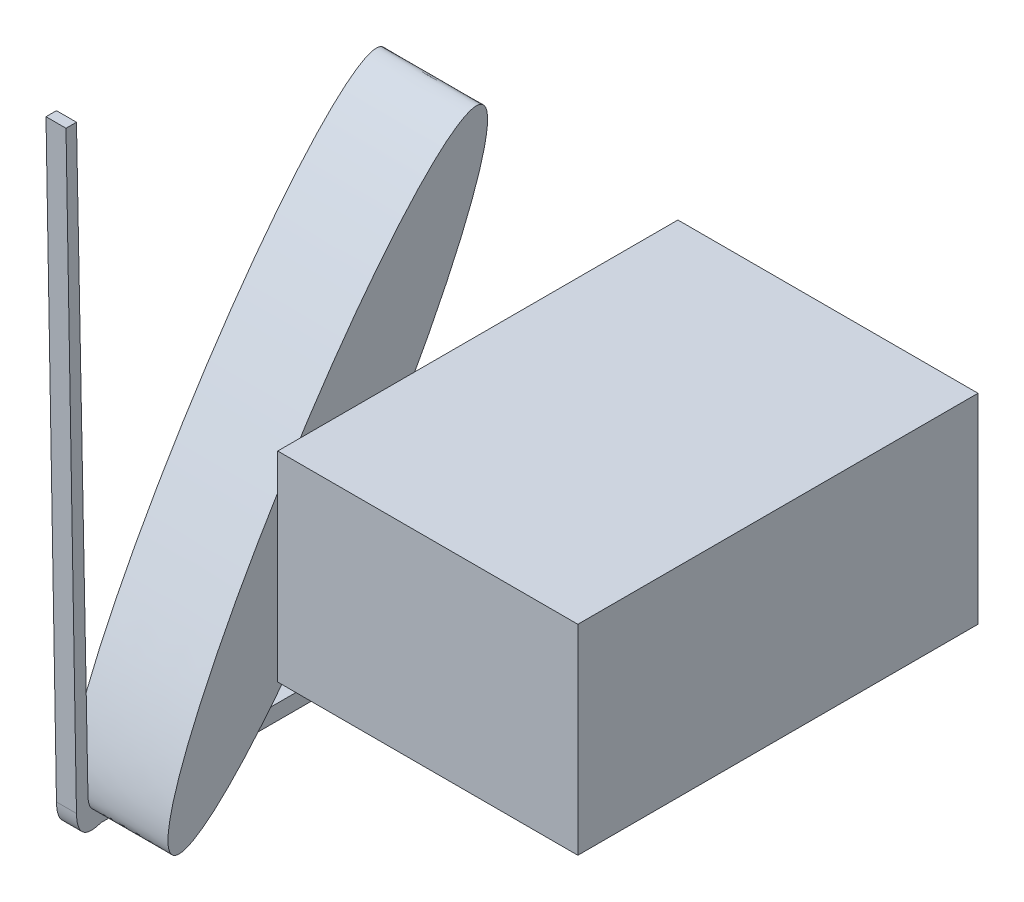
SolidWorks part; units mm, degrees
ref_plane "前视基准面" through (0, 0, 0) normal (0, 0, 1) x (1, 0, 0)
ref_plane "上视基准面" through (0, 0, 0) normal (0, 1, 0) x (1, 0, 0)
ref_plane "右视基准面" through (0, 0, 0) normal (1, 0, 0) x (0, 0, -1)
sketch "草图1" plane through (0, 0, 0) normal (0, 0, 1) x (1, 0, 0)
  line L1 (0, 0) -> (30, 0)
  line L2 (0, 0) -> (0, 20)
  line L3 (0, 20) -> (30, 20)
  line L4 (30, 0) -> (30, 20)
extrude "凸台-拉伸1" add sketch "草图1" along normal blind 40
sketch "草图2" plane through (0, 0, 0) normal (-1, 0, 0) x (0, 0, 1)
  circle A0 centre (30, 10) radius 2
extrude "凸台-拉伸2" add sketch "草图2" along normal blind 5
sketch "草图3" plane through (-5, 0, 0) normal (-1, 0, 0) x (0, 0, 1)
  ellipse E0 centre (30, 10) end of major axis (45.3967, -14.8161) minor radius 5
  point P1 (14.6033, 34.8161)
extrude "凸台-拉伸4" add sketch "草图3" along normal blind 10
sketch "草图4" plane through (-15, 0, 0) normal (-1, 0, 0) x (0, 0, 1)
  line L0 (46.3434, -16.3419) -> (0, -16.3419)
  line L1 (45.3967, -14.8161) -> (0, -14.8161)
  line L2 (0, -14.8161) -> (0, -16.3419)
  line L3 (47.1192, -14.3208) -> (48.1652, 45.5236)
  line L4 (45.9713, -13.3187) -> (47.1192, 45.5236)
  line L5 (47.1192, 45.5236) -> (48.1652, 45.5236)
  ellipse E0 centre (30, 10) end of major axis (46.3434, -16.3419) minor radius 6
  ellipse E1 centre (30, 10) end of major axis (14.6033, 34.8161) minor radius 5 construction
  ellipse M2 centre (30, 10) end of major axis (14.6033, 34.8161) minor radius 5
extrude "凸台-拉伸5" add sketch "草图4" against normal blind 2 contours L0 E0 | L0 E0 L4 L1 M2 | E0 L1 L2 L0 | E0 L3 L5 L4
